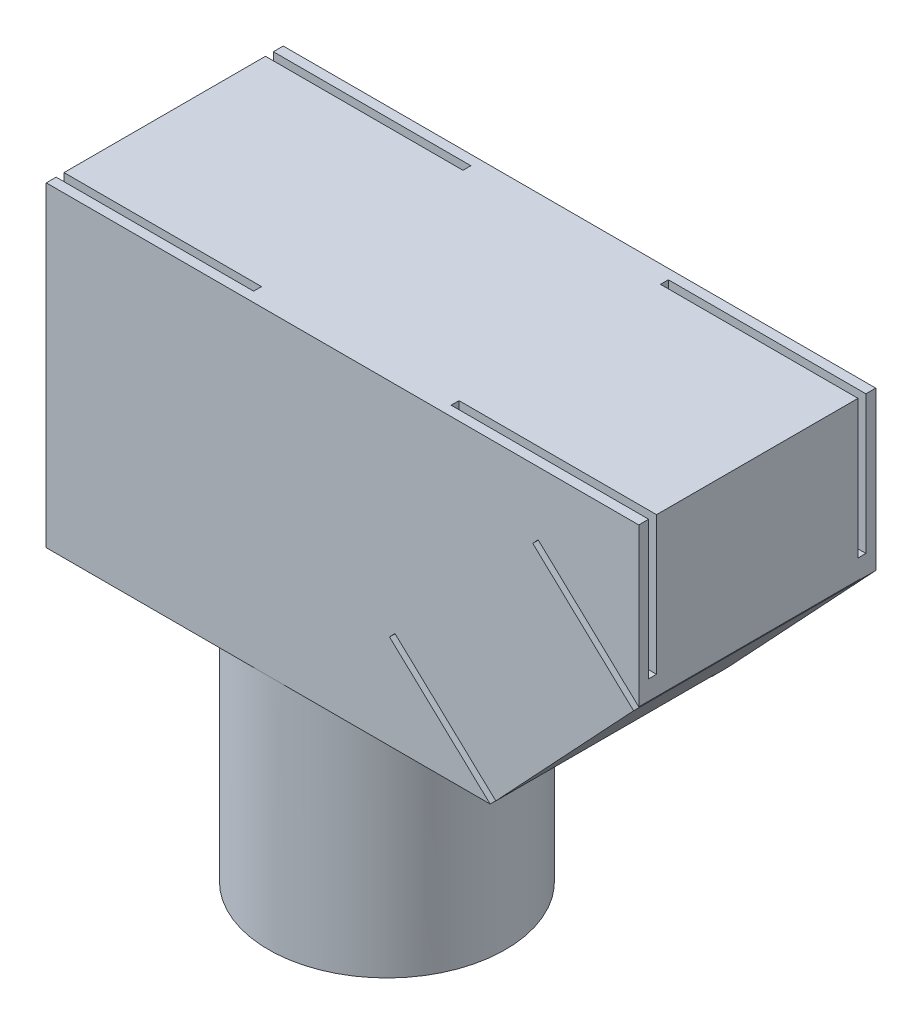
SolidWorks part; units mm, degrees
ref_plane "前视基准面" through (0, 0, 0) normal (0, 0, 1) x (1, 0, 0)
ref_plane "上视基准面" through (0, 0, 0) normal (0, 1, 0) x (1, 0, 0)
ref_plane "右视基准面" through (0, 0, 0) normal (1, 0, 0) x (0, 0, -1)
sketch "草图1" plane through (0, 0, 0) normal (0, 0, 1) x (1, 0, 0)
  line L0 (0, 0) -> (50000, 0) construction
  line L1 (0, 0) -> (0, 50000) construction
  line L3 (-75, 40) -> (75, 40)
  line L4 (-75, 40) -> (-75, -40)
  line L5 (-75, -40) -> (75, -40)
  line L6 (75, 40) -> (75, -40)
extrude "凸台-拉伸1" add sketch "草图1" along normal blind 60
sketch "草图2" plane through (0, 0, 60) normal (0, 0, 1) x (1, 0, 0)
  line L0 (75, 0) -> (50075, 0) construction
  line L1 (75, -40) -> (75, 40) construction
  line L2 (0, 0) -> (0, 50000) construction
  line L3 (37.5, -40) -> (37.5, 0)
  line L4 (-75, -40) -> (75, -40) construction
  line L5 (75, 0) -> (37.5, -40)
  line L6 (37.5, 0) -> (75, 0)
  line L7 (37.5, 0) -> (37.5, -40)
  line L8 (37.5, -40) -> (75, -40)
  line L9 (75, 0) -> (75, -40)
  point P4 (75, 0)
  line M4 (-75, -40) -> (75, -40)
  line M5 (75, -40) -> (75, 40)
  dimension "D1" = 37.5
extrude "切除-拉伸2" cut sketch "草图2" against normal blind 60 contours L5 M5 M4
sketch "草图3" plane through (0, 40, 0) normal (0, 1, 0) x (1, 0, 0)
  line L0 (-75, -30) -> (49925, -30) construction
  line L1 (-75, -60) -> (-75, 0) construction
  line L2 (0, 0) -> (0, -50000) construction
  line L3 (75, 0) -> (-75, 0) construction
  line L4 (-75, -55.5) -> (-25, -55.5)
  line L5 (-75, -2.5) -> (-25, -2.5)
  line L6 (-75, -2.5) -> (-75, -4.5)
  line L7 (-75, -4.5) -> (-25, -4.5)
  line L8 (-25, -2.5) -> (-25, -4.5)
  line L9 (-25, -57.5) -> (-25, -55.5)
  line L10 (-75, -57.5) -> (-75, -55.5)
  line L11 (-75, -57.5) -> (-25, -57.5)
  line L12 (75, -57.5) -> (75, -55.5)
  line L13 (75, -57.5) -> (25, -57.5)
  line L14 (25, -57.5) -> (25, -55.5)
  line L15 (75, -55.5) -> (25, -55.5)
  line L16 (75, -4.5) -> (25, -4.5)
  line L17 (25, -2.5) -> (25, -4.5)
  line L18 (75, -2.5) -> (25, -2.5)
  line L19 (75, -2.5) -> (75, -4.5)
  point P4 (-75, -30)
  point P9 (0, 0)
  dimension "D1" = 51
  dimension "D2" = 2
extrude "切除-拉伸3" cut sketch "草图3" against normal blind 35
sketch "草图4" plane through (39.9168, -37.422, 0) normal (0.7295, -0.6839, 0) x (0, 0, -1)
  line L0 (-30, 51.2956) -> (-30, 50051.2956) construction
  line L1 (0, 51.2956) -> (-60, 51.2956) construction
  line L2 (-60, 23.8809) -> (49940, 23.8809) construction
  line L3 (-60, 51.2956) -> (-60, -3.5337) construction
  line L4 (-2, -1.1191) -> (-4, -1.1191)
  line L5 (-58, 48.8809) -> (-56, 48.8809)
  line L6 (-58, 48.8809) -> (-58, -1.1191)
  line L7 (-58, -1.1191) -> (-56, -1.1191)
  line L8 (-56, 48.8809) -> (-56, -1.1191)
  line L9 (-4, 48.8809) -> (-4, -1.1191)
  line L10 (-2, 48.8809) -> (-4, 48.8809)
  line L11 (-2, 48.8809) -> (-2, -1.1191)
  point P4 (-30, 51.2956)
  point P9 (-60, 23.8809)
  dimension "D1" = 2
  dimension "D2" = 50
  dimension "D3" = 2
extrude "切除-拉伸4" cut sketch "草图4" against normal blind 35
sketch "草图5" plane through (0, -40, 0) normal (0, -1, 0) x (1, 0, 0)
  line L0 (-18.75, 0) -> (-18.75, 50000) construction
  line L1 (-75, 0) -> (37.5, 0) construction
  line L2 (-75, 30) -> (49925, 30) construction
  line L3 (-75, 60) -> (-75, 0) construction
  circle A0 centre (-18.75, 30) radius 30
  point P4 (-18.75, 0)
  point P9 (-75, 30)
extrude "凸台-拉伸2" add sketch "草图5" along normal blind 60 contours A0
sketch "草图6" plane through (0, 0, 0) normal (0, 0, -1) x (-1, 0, 0)
  line L0 (75, 40) -> (75, -40) construction
  line L1 (73, 38) -> (-73, 38)
  line L2 (73, 38) -> (73, -38)
  line L3 (73, -38) -> (-73, -38)
  line L4 (-73, 38) -> (-73, -38)
  line L5 (-75, 40) -> (75, 40) construction
  line L6 (75, -40) -> (18.75, -40) construction
  line L7 (-75, 0) -> (-75, 40) construction
  line L8 (-73, 0.7909) -> (-36.6335, -38)
  line L9 (-75, 0) -> (-37.5, -40) construction
  dimension "D1" = 2
  dimension "D2" = 2
  dimension "D3" = 2
  dimension "D4" = 2
  dimension "D5" = 2
extrude "切除-拉伸5" cut sketch "草图6" against normal blind 58 contours L4 L8 L3 L2 L1
sketch "草图7" plane through (0, -100, 0) normal (0, -1, 0) x (1, 0, 0)
  line L0 (-48.75, 30) -> (49951.25, 30) construction
  line L1 (-18.75, 30) -> (-18.75, 50030) construction
  arc A0 (-18.75, 60) -> (-18.75, 0) centre (-18.75, 30) ccw construction
  circle A1 centre (-18.75, 30) radius 20
  point P5 (-48.75, 30)
extrude "切除-拉伸8" cut sketch "草图7" against normal blind 62
sketch "草图8" plane through (39.9168, -37.422, 0) normal (0.7295, -0.6839, 0) x (0, 0, -1)
  line L1 (-58, 48.8809) -> (-56, 48.8809)
  line L2 (-58, 48.8809) -> (-58, -1.1191)
  line L3 (-58, -1.1191) -> (-56, -1.1191)
  line L4 (-56, 48.8809) -> (-56, -1.1191)
  line L5 (-4, 48.8809) -> (-2, 48.8809)
  line L6 (-4, 48.8809) -> (-4, -1.1191)
  line L7 (-4, -1.1191) -> (-2, -1.1191)
  line L8 (-2, 48.8809) -> (-2, -1.1191)
  line L13 (-56, 23.8809) -> (49944, 23.8809) construction
  line L18 (-4, 51.3809) -> (-62.2875, 51.3809)
  line L19 (-4, -1.6191) -> (-62.2875, -1.6191)
  line L20 (-4, -1.6191) -> (-4, -3.6191)
  line L21 (-4, -3.6191) -> (-62.2875, -3.6191)
  line L22 (-62.2875, -1.6191) -> (-62.2875, -3.6191)
  line L23 (-62.2875, 49.3809) -> (-62.2875, 51.3809)
  line L24 (-4, 49.3809) -> (-62.2875, 49.3809)
  line L25 (-4, 49.3809) -> (-4, 51.3809)
  point P19 (-56, 23.8809)
  dimension "D1" = 51
extrude "切除-拉伸12" cut sketch "草图8" against normal blind 35 contours L20 L19 L22 L21 | L18 L23 L24 L25
sketch "草图10" plane through (39.9168, -37.422, 0) normal (0.7295, -0.6839, 0) x (0, 0, -1)
  line L1 (-58, 48.8809) -> (-56, 48.8809)
  line L2 (-58, 48.8809) -> (-58, -1.1191)
  line L3 (-58, -1.1191) -> (-56, -1.1191)
  line L4 (-56, 48.8809) -> (-56, -1.1191)
  line L5 (-2, 48.8809) -> (-4, 48.8809)
  line L6 (-2, 48.8809) -> (-2, -1.1191)
  line L7 (-2, -1.1191) -> (-4, -1.1191)
  line L8 (-4, 48.8809) -> (-4, -1.1191)
extrude "凸台-拉伸6" add sketch "草图10" against normal blind 2
